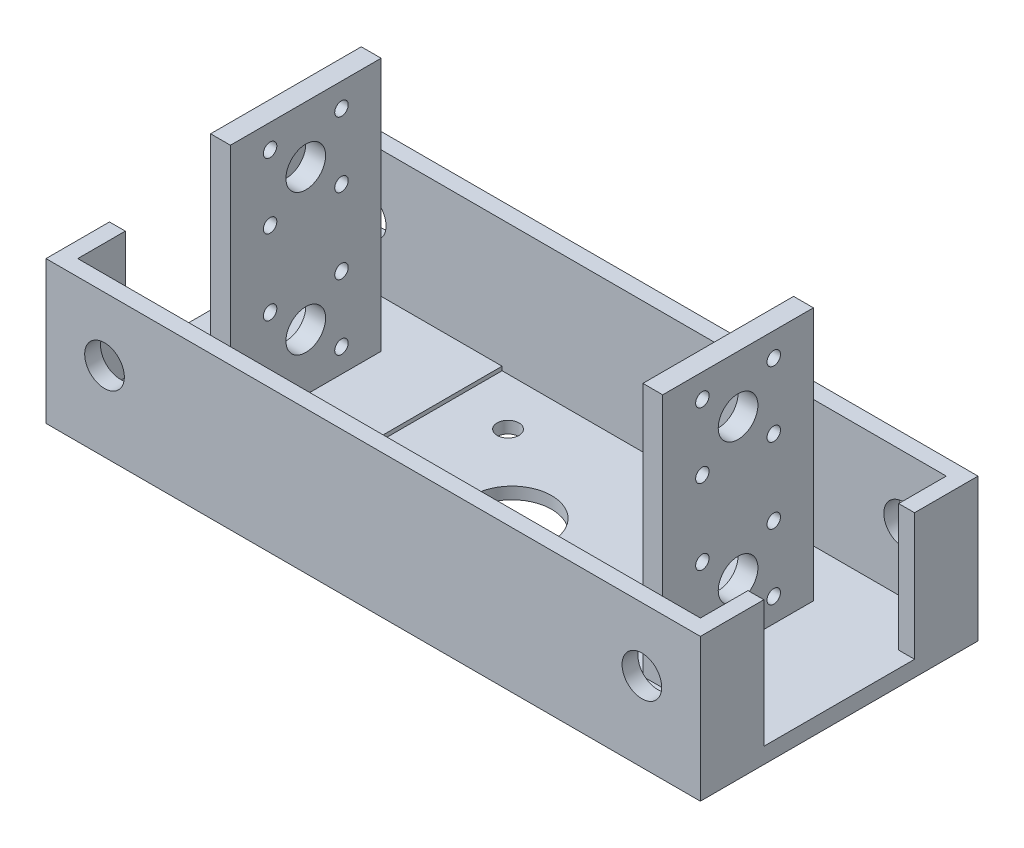
SolidWorks part; units mm, degrees
ref_plane "Front Plane" through (0, 0, 0) normal (0, 0, 1) x (1, 0, 0)
ref_plane "Top Plane" through (0, 0, 0) normal (0, 1, 0) x (1, 0, 0)
ref_plane "Right Plane" through (0, 0, 0) normal (1, 0, 0) x (0, 0, -1)
sketch "Sketch1" plane through (0, 0, 0) normal (0, 1, 0) x (1, 0, 0)
  line L0 (0, 0) -> (0, -14.43) construction
  line L1 (-37.5, 20) -> (37.5, 20)
  line L2 (-37.5, 20) -> (-37.5, -20)
  line L3 (-37.5, -20) -> (37.5, -20)
  line L4 (37.5, 20) -> (37.5, -20)
  line L5 (-37.5, 20) -> (37.5, -20) construction
  line L6 (-37.5, -20) -> (37.5, 20) construction
  line L7 (0, 0) -> (6.508, 0) construction
  line L8 (-5, 10) -> (5, 10)
  line L9 (-5, 10) -> (-5, -10)
  line L10 (-5, -10) -> (5, -10)
  line L11 (5, 10) -> (5, -10)
  line L12 (-5, 10) -> (5, -10) construction
  line L13 (-5, -10) -> (5, 10) construction
  circle A0 centre (-21, 0) radius 5
  circle A1 centre (-30, 8.25) radius 1.7
  circle A2 centre (-12, 8.25) radius 1.7
  circle A3 centre (-12, -8.25) radius 1.7
  circle A4 centre (-30, -8.25) radius 1.7
  circle A5 centre (12, 8.25) radius 1.7
  circle A6 centre (12, -8.25) radius 1.7
  circle A7 centre (21, 0) radius 5
  circle A8 centre (30, -8.25) radius 1.7
  circle A9 centre (30, 8.25) radius 1.7
  point P0 (0, 0)
  dimension "D3" = 10
  dimension "D4" = 16.5
  dimension "D5" = 16.5
  dimension "D6" = 18
  dimension "D9" = 10
  dimension "D11" = 20
  dimension "D13" = 7.5
  dimension "D17" = 3.4
  dimension "D19" = 11.75
  dimension "D20" = 11.75
  dimension "D1" = 75
  dimension "D2" = 40
  dimension "D10" = 10
  dimension "D7" = 2
  dimension "D8" = 2
extrude "Boss-Extrude1" add sketch "Sketch1" along normal blind 3
sketch "Sketch2" plane through (0, 3, 0) normal (0, 1, 0) x (1, 0, 0)
  line L0 (-37.5, 20) -> (-37.5, -20) construction
  line L1 (-33.5, 14) -> (33.5, 14)
  line L2 (-33.5, 14) -> (-33.5, -14)
  line L3 (-33.5, -14) -> (33.5, -14)
  line L4 (33.5, 14) -> (33.5, -14)
  line L5 (37.5, -20) -> (37.5, 20) construction
  line L6 (37.5, 20) -> (-37.5, 20) construction
  line L7 (-37.5, -20) -> (37.5, -20) construction
  dimension "D1" = 4
  dimension "D2" = 4
  dimension "D3" = 6
  dimension "D4" = 6
extrude "Cut-Extrude1" cut sketch "Sketch2" against normal through all both and the other way through all
sketch "Sketch3" plane through (0, 3, 0) normal (0, 1, 0) x (1, 0, 0)
  line L1 (37.5, 20) -> (-37.5, 20)
  line L2 (37.5, 20) -> (37.5, 35)
  line L3 (37.5, 35) -> (-37.5, 35)
  line L4 (-37.5, 20) -> (-37.5, 35)
  line L5 (-37.5, -20) -> (37.5, -20)
  line L6 (-37.5, -20) -> (-37.5, -35)
  line L7 (-37.5, -35) -> (37.5, -35)
  line L8 (37.5, -20) -> (37.5, -35)
  line L10 (-37.5, 20) -> (-33.5, 20)
  line L11 (-37.5, 20) -> (-37.5, -20)
  line L12 (-37.5, -20) -> (-33.5, -20)
  line L13 (-33.5, 20) -> (-33.5, -20)
  line L14 (37.5, 20) -> (33.5, 20)
  line L15 (37.5, 20) -> (37.5, -20)
  line L16 (37.5, -20) -> (33.5, -20)
  line L17 (33.5, 20) -> (33.5, -20)
  line M3 (-33.5, -14) -> (-33.5, 14)
  line M5 (33.5, 14) -> (33.5, -14)
  line M11 (37.5, -20) -> (37.5, 20)
  line M12 (37.5, 20) -> (-37.5, 20)
  line M13 (-37.5, 20) -> (-37.5, -20)
  line M14 (-37.5, -20) -> (37.5, -20)
  dimension "D1" = 15
  dimension "D2" = 15
extrude "Boss-Extrude3" add sketch "Sketch3" along normal blind 110 and the other way blind 3 contours L8 L5 L6 L7 M14 | L4 L1 L2 L3 M12 | L17 M12 M5 M14 M11 | L13 L1 M13 M14 M3
sketch "Sketch6" plane through (0, 3, 0) normal (0, 1, 0) x (1, 0, 0)
  line L0 (-37.5, -35) -> (37.5, -35) construction
  line L1 (-33.5, -20) -> (33.5, -20)
  line L2 (-33.5, -20) -> (-33.5, -31)
  line L3 (-33.5, -31) -> (33.5, -31)
  line L4 (33.5, -20) -> (33.5, -31)
  line L5 (33.5, 20) -> (-33.5, 20)
  line L6 (33.5, 20) -> (33.5, 31)
  line L7 (33.5, 31) -> (-33.5, 31)
  line L8 (-33.5, 20) -> (-33.5, 31)
  line L9 (37.5, 35) -> (-37.5, 35) construction
  dimension "D1" = 4
  dimension "D2" = 4
extrude "Cut-Extrude4" cut sketch "Sketch6" along normal through all
sketch "Sketch7" plane through (-37.5, 0, 0) normal (-1, 0, 0) x (0, 0, 1)
  line L0 (35, 0) -> (35, 113) construction
  line L1 (-35, 113) -> (35, 113)
  line L2 (-35, 113) -> (-35, 76)
  line L3 (-35, 76) -> (35, 76)
  line L4 (35, 113) -> (35, 76)
  dimension "D1" = 37
extrude "Boss-Extrude4" add sketch "Sketch7" along normal blind 45
ref_plane "Plane1" through (0, 0, 0) normal (1, 0, 0) x (0, 0, -1)
mirror "Mirror2" about plane through (0, 0, 0) normal (1, 0, 0) of "Boss-Extrude4"
sketch "Sketch8" plane through (0, 113, 0) normal (0, 1, 0) x (1, 0, 0)
  line L0 (-82.5, -35) -> (-82.5, 35) construction
  line L1 (-33.5, 31) -> (-78.5, 31)
  line L2 (-33.5, 31) -> (-33.5, -31)
  line L3 (-33.5, -31) -> (-78.5, -31)
  line L4 (-78.5, 31) -> (-78.5, -31)
  line L5 (33.5, -31) -> (78.5, -31)
  line L6 (33.5, -31) -> (33.5, 31)
  line L7 (33.5, 31) -> (78.5, 31)
  line L8 (78.5, -31) -> (78.5, 31)
  line L9 (82.5, -35) -> (82.5, 35) construction
  dimension "D1" = 4
  dimension "D2" = 4
extrude "Cut-Extrude6" cut sketch "Sketch8" against normal blind 29
sketch "Sketch9" plane through (-82.5, 0, 0) normal (-1, 0, 0) x (0, 0, 1)
  line L18 (-31, 84) -> (31, 84) construction
  line L19 (-19, 84) -> (19, 84)
  line L20 (-19, 84) -> (-19, 112.5)
  line L21 (-19, 112.5) -> (19, 112.5)
  line L22 (19, 84) -> (19, 112.5)
  line L25 (-31, 84) -> (-31, 113) construction
  dimension "D1" = 38
  dimension "D2" = 12
  dimension "D3" = 28.5
sketch "Sketch11" plane through (0, 0, 35) normal (0, 0, 1) x (1, 0, 0)
  line L0 (82.5, 76) -> (82.5, 113) construction
  line L1 (-82.5, 76) -> (-37.5, 76)
  line L2 (-82.5, 76) -> (-82.5, 80)
  line L3 (-82.5, 80) -> (-37.5, 80)
  line L4 (-37.5, 76) -> (-37.5, 80)
  line L5 (37.5, 76) -> (82.5, 76)
  line L6 (37.5, 76) -> (37.5, 80)
  line L7 (37.5, 80) -> (82.5, 80)
  line L8 (82.5, 76) -> (82.5, 80)
  line L11 (-78.5, 84) -> (-33.5, 84) construction
  line L12 (33.5, 84) -> (78.5, 84) construction
  dimension "D1" = 4
  dimension "D2" = 4
extrude "Cut-Extrude9" cut sketch "Sketch11" against normal through all
extrude "Cut-Extrude10" cut sketch "Sketch9" against normal through all
sketch "Sketch13" plane through (0, 84, 0) normal (0, 1, 0) x (1, 0, 0)
  line L0 (-78.5, 31) -> (-78.5, -31) construction
  line L1 (-57, 19) -> (-52, 19)
  line L2 (-57, 19) -> (-57, -19)
  line L3 (-57, -19) -> (-52, -19)
  line L4 (-52, 19) -> (-52, -19)
  line L7 (78.5, 31) -> (-78.5, 31) construction
  line L13 (-57, -19) -> (-57, 19)
  line L17 (-82.5, -19) -> (-107.5, -19)
  line L18 (-82.5, -19) -> (-82.5, 19)
  line L19 (-82.5, 19) -> (-107.5, 19)
  line L20 (-107.5, -19) -> (-107.5, 19)
  line L21 (-107.5, 19) -> (-61, 19)
  line L22 (-107.5, 19) -> (-107.5, -19)
  line L23 (-107.5, -19) -> (-61, -19)
  line L24 (-61, 19) -> (-61, -19)
  dimension "D1" = 21.5
  dimension "D2" = 5
  dimension "D3" = 38
  dimension "D4" = 12
  dimension "D5" = 25
  dimension "D6" = 46.5
extrude "Boss-Extrude5" add sketch "Sketch13" along normal blind 32 contours L4 L1 L2 L3
sketch "Sketch14" plane through (-57, 0, 0) normal (-1, 0, 0) x (0, 0, 1)
  line L0 (-19, 116) -> (-19, 84) construction
  line L4 (19, 112.5) -> (-19, 112.5) construction
  circle A0 centre (0, 98.25) radius 5
  circle A1 centre (-9, 106.5) radius 1.7
  circle A2 centre (9, 106.5) radius 1.7
  circle A3 centre (9, 90) radius 1.7
  circle A4 centre (-9, 90) radius 1.7
  dimension "D1" = 19
  dimension "D2" = 9
  dimension "D3" = 10
  dimension "D6" = 3.4
  dimension "D7" = 14.25
  dimension "D8" = 16.5
  dimension "D9" = 18
  dimension "D10" = 8.25
  dimension "D4" = 2
  dimension "D5" = 2
extrude "Cut-Extrude11" cut sketch "Sketch14" against normal blind 32
mirror "Mirror4" about plane through (0, 0, 0) normal (1, 0, 0) of "Boss-Extrude5", "Cut-Extrude11"
sketch "Sketch15" plane through (0, 113, 0) normal (0, 1, 0) x (1, 0, 0)
  line L1 (-82.5, 35) -> (82.5, 35)
  line L2 (-82.5, 35) -> (-82.5, -35)
  line L3 (-82.5, -35) -> (82.5, -35)
  line L4 (82.5, 35) -> (82.5, -35)
  line L5 (-78.5, 31) -> (78.5, 31)
  line L6 (-78.5, 31) -> (-78.5, -31)
  line L7 (-78.5, -31) -> (78.5, -31)
  line L8 (78.5, 31) -> (78.5, -31)
extrude "Boss-Extrude6" add sketch "Sketch15" along normal blind 3
sketch "Sketch16" plane through (0, 0, 35) normal (0, 0, 1) x (1, 0, 0)
  line L1 (-10, 14.0464) -> (10, 14.0464)
  line L2 (-10, 14.0464) -> (-10, 9.2258)
  line L3 (-10, 9.2258) -> (10, 9.2258)
  line L4 (10, 14.0464) -> (10, 9.2258)
  line L5 (-37.5, 0) -> (-37.5, 80) construction
  dimension "D1" = 20
  dimension "D2" = 27.5
extrude "Cut-Extrude12" cut sketch "Sketch16" against normal through all
sketch "Sketch18" plane through (0, 0, 35) normal (0, 0, 1) x (1, 0, 0)
  line L0 (57, 116) -> (57, 84) construction
  line L2 (33.5, 84) -> (78.5, 84) construction
  circle A0 centre (67.75, 100) radius 5
  dimension "D1" = 10.75
  dimension "D2" = 16
  dimension "D3" = 10
extrude "Cut-Extrude14" cut sketch "Sketch18" against normal through all
mirror "Mirror5" about plane through (0, 0, 0) normal (1, 0, 0) of "Cut-Extrude14"
mirror "Mirror6" about plane through (0, 116, 0) normal (0, 1, 0) of "Mirror4", "Boss-Extrude5", "Cut-Extrude11"
sketch "Sketch19" plane through (82.5, 0, 0) normal (1, 0, 0) x (0, 0, -1)
  line L0 (19, 148) -> (19, 84) construction
  line L1 (-19, 112.5) -> (19, 112.5)
  line L2 (-19, 112.5) -> (-19, 116)
  line L3 (-19, 116) -> (19, 116)
  line L4 (19, 112.5) -> (19, 116)
extrude "Cut-Extrude15" cut sketch "Sketch19" against normal blind 10
mirror "Mirror7" about plane through (0, 0, 0) normal (1, 0, 0) of "Cut-Extrude15"
sketch "Sketch20" plane through (0, 3, 0) normal (0, 1, 0) x (1, 0, 0)
  line L0 (33.5, 31) -> (-33.5, 31) construction
  line L1 (-5, -10) -> (5, -10)
  line L2 (-5, -10) -> (-5, 10)
  line L3 (-5, 10) -> (5, 10)
  line L4 (5, -10) -> (5, 10)
  line L5 (-5, -10) -> (5, 10) construction
  line L6 (-5, 10) -> (5, -10) construction
  line L7 (0, 0) -> (0, 17.5) construction
  line L8 (-37.5, 20) -> (37.5, 20)
  line L9 (-37.5, 20) -> (-37.5, -20)
  line L10 (-37.5, -20) -> (37.5, -20)
  line L11 (37.5, 20) -> (37.5, -20)
  line L12 (-37.5, 20) -> (37.5, -20) construction
  line L13 (-37.5, -20) -> (37.5, 20) construction
  line L14 (0, -34.1) -> (0, 34.1) construction
  circle A1 centre (-12, 17.5) radius 1.2
  circle A2 centre (-12, -17.5) radius 1.2
  circle A3 centre (-24, -17.5) radius 1.2
  circle A4 centre (-24, 17.5) radius 1.2
  circle A5 centre (12, -17.5) radius 1.2
  circle A6 centre (24, -17.5) radius 1.2
  circle A7 centre (12, 17.5) radius 1.2
  circle A8 centre (24, 17.5) radius 1.2
  point P2 (0, 0)
  point P10 (0, 0)
  dimension "D1" = 7
  dimension "D2" = 10
  dimension "D4" = 2.5
  dimension "D7" = 35
  dimension "D8" = 7
  dimension "D9" = 2.4
  dimension "D11" = 12
  dimension "D3" = 21
  dimension "D5" = 75
  dimension "D6" = 40
  dimension "D10" = 2
extrude "Cut-Extrude16" cut sketch "Sketch20" against normal blind 10 contours A4 | A1 | A7 | A3 | A2 | A8 | A5 | A6
sketch "Sketch21" plane through (0, 0, 35) normal (0, 0, 1) x (1, 0, 0)
  line L0 (0, -34.1) -> (0, 34.1) construction
  line L1 (37.5, 0) -> (27.5, 0)
  line L2 (37.5, 0) -> (37.5, 80)
  line L3 (37.5, 80) -> (27.5, 80)
  line L4 (27.5, 0) -> (27.5, 80)
  line L5 (-27.5, 0) -> (-27.5, 80)
  line L6 (-37.5, 80) -> (-27.5, 80)
  line L7 (-37.5, 0) -> (-37.5, 80)
  line L8 (-37.5, 0) -> (-27.5, 0)
  dimension "D1" = 10
  dimension "D2" = 80
extrude "Cut-Extrude17" cut sketch "Sketch21" against normal through all
sketch "Sketch22" plane through (0, 0, 35) normal (0, 0, 1) x (1, 0, 0)
  line L1 (-27.5, 0) -> (27.5, 0)
  line L2 (-27.5, 0) -> (-27.5, 80)
  line L3 (-27.5, 80) -> (27.5, 80)
  line L4 (27.5, 0) -> (27.5, 80)
extrude "Cut-Extrude18" cut sketch "Sketch22" against normal through all
sketch "Sketch23" plane through (0, 80, 0) normal (0, -1, 0) x (1, 0, 0)
  line L1 (-33.5, 31) -> (33.5, 31)
  line L2 (-33.5, 31) -> (-33.5, -31)
  line L3 (-33.5, -31) -> (33.5, -31)
  line L4 (33.5, 31) -> (33.5, -31)
extrude "Boss-Extrude7" add sketch "Sketch23" against normal blind 3
sketch "Sketch24" plane through (0, 83, 0) normal (0, 1, 0) x (1, 0, 0)
  line L5 (78.5, 31) -> (-78.5, 31) construction
  line L9 (33.5, -31) -> (-33.5, -31) construction
  line L10 (0, 0) -> (0, 16.8876) construction
  line L11 (0, -34.1) -> (0, 34.1) construction
  circle A0 centre (0, 0) radius 10
  circle A1 centre (-20, 19) radius 2.75
  circle A2 centre (-20, -19) radius 2.75
  circle A3 centre (20, -19) radius 2.75
  circle A4 centre (20, 19) radius 2.75
  dimension "D1" = 20
  dimension "D2" = 12
  dimension "D3" = 20
  dimension "D4" = 12
extrude "Cut-Extrude19" cut sketch "Sketch24" against normal through all
